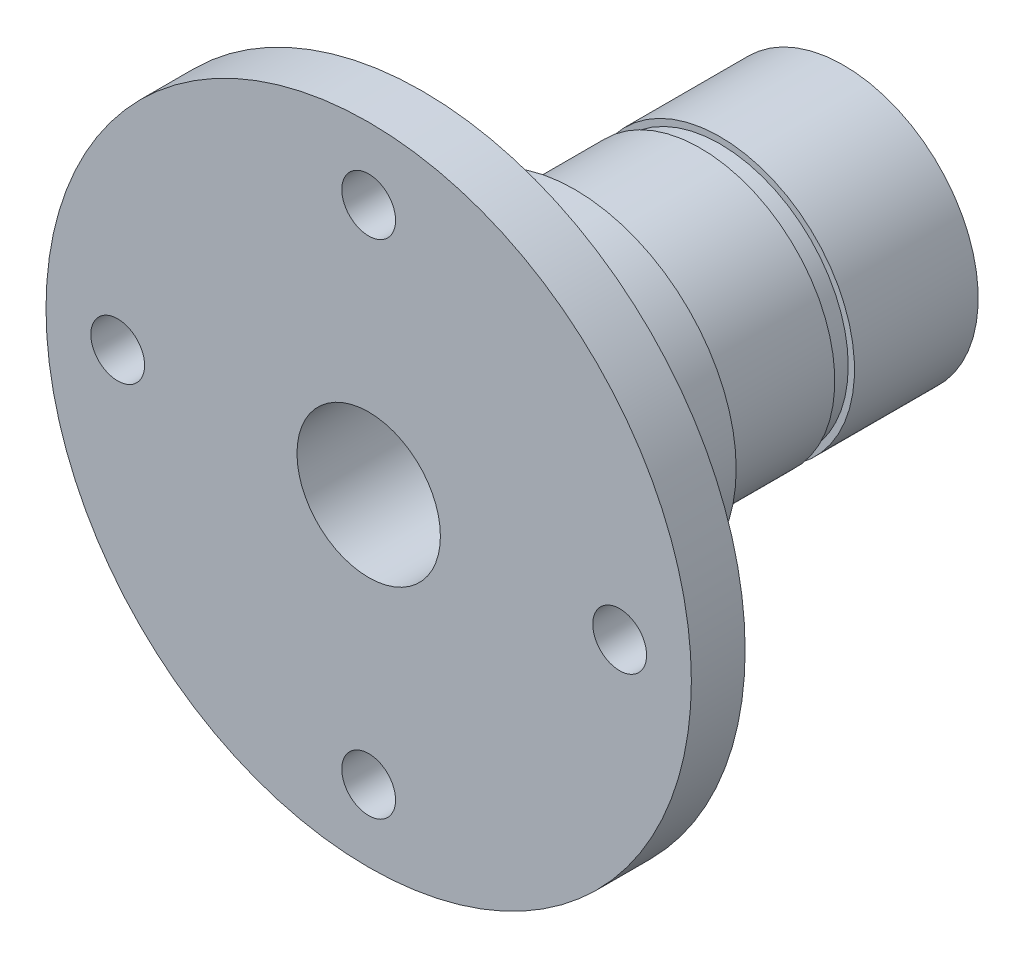
SolidWorks part; units mm, degrees
material "6061 合金"
ref_plane "前视基准面" through (0, 0, 0) normal (0, 0, 1) x (1, 0, 0)
ref_plane "上视基准面" through (0, 0, 0) normal (0, 1, 0) x (1, 0, 0)
ref_plane "右视基准面" through (0, 0, 0) normal (1, 0, 0) x (0, 0, -1)
sketch "草图1" plane through (0, 0, 0) normal (0, 0, 1) x (1, 0, 0)
  circle A1 centre (0, 0) radius 18
  circle A2 centre (0, 0) radius 14 construction
  circle A3 centre (0, 14) radius 1.5
  circle A4 centre (14, 0) radius 1.5
  circle A5 centre (0, -14) radius 1.5
  circle A6 centre (-14, 0) radius 1.5
  circle A7 centre (0, 0) radius 4
  point P18 (0, 0)
  dimension "D1" = 4
extrude "凸台-拉伸1" add sketch "草图1" along normal blind 3
sketch "草图2" plane through (0, 0, 0) normal (0, 0, -1) x (-1, 0, 0)
  circle A0 centre (0, 0) radius 9
  circle A3 centre (0, 0) radius 4
extrude "凸台-拉伸2" add sketch "草图2" along normal blind 8.5
sketch "草图3" plane through (0, 0, -8.5) normal (0, 0, -1) x (-1, 0, 0)
  circle A0 centre (0, 0) radius 7.5
  circle A3 centre (0, 0) radius 4
extrude "凸台-拉伸3" add sketch "草图3" along normal blind 15
ref_plane "基准面1" through (0, 0, -15.5) normal (0, 0, -1) x (-1, 0, 0)
sketch "草图4" plane through (0, 0, -15.5) normal (0, 0, -1) x (-1, 0, 0)
  circle A0 centre (0, 0) radius 7.15
  circle A1 centre (0, 0) radius 7.5
extrude "切除-拉伸2" cut sketch "草图4" along normal blind 1.1
sketch "草图5" plane through (0, 0, 0) normal (0, 1, 0) x (1, 0, 0)
  line L0 (-7.15, 16.6) -> (7.15, 16.6) construction
  line L1 (-7.15, 16.6) -> (7.15, 16.6) construction
  line L2 (0, 16.6) -> (0, 20.6) construction
  circle A0 centre (0, 20.6) radius 1.5
extrude "切除-拉伸3" cut sketch "草图5" against normal up to surface (7.5 mm away)
sketch "草图7" plane through (0, 0, 0) normal (1, 0, 0) x (0, 0, -1)
  line L0 (16.6, 7.5) -> (16.6, -7.5) construction
  line L1 (16.6, 7.5) -> (16.6, -7.5) construction
  line L2 (16.6, 0) -> (20.6, 0) construction
  circle A0 centre (20.6, 0) radius 1.5
extrude "切除-拉伸4" cut sketch "草图7" against normal up to surface (7.5 mm away)
